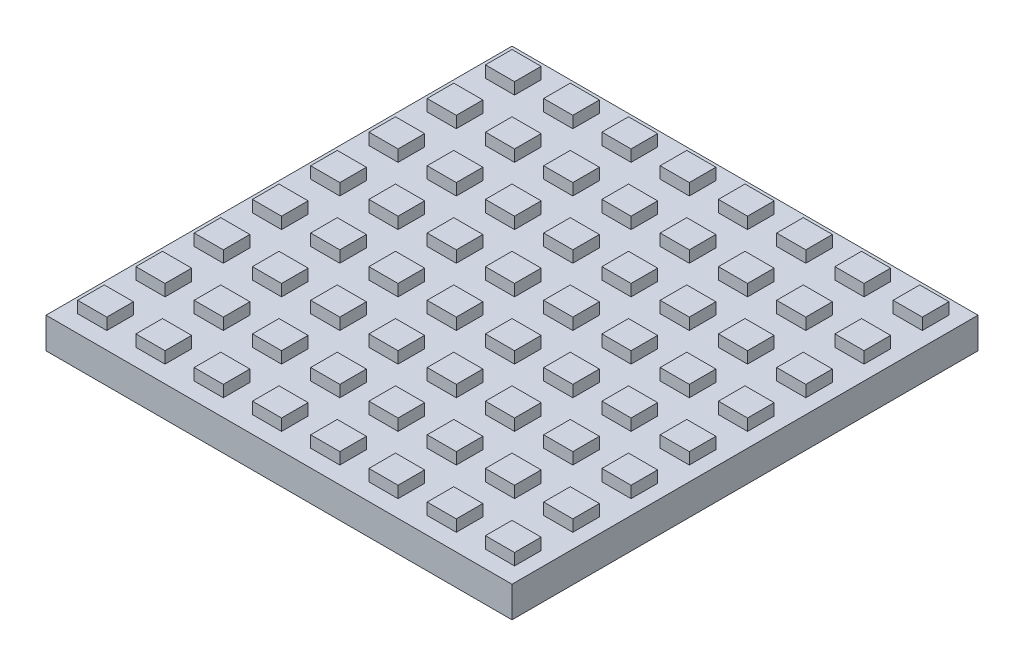
SolidWorks part; units mm, degrees
ref_plane "Front Plane" through (0, 0, 0) normal (0, 0, 1) x (1, 0, 0)
ref_plane "Top Plane" through (0, 0, 0) normal (0, 1, 0) x (1, 0, 0)
ref_plane "Right Plane" through (0, 0, 0) normal (1, 0, 0) x (0, 0, -1)
sketch "Sketch1" plane through (0, 0, 0) normal (0, 1, 0) x (1, 0, 0)
  line L1 (0, 0) -> (80, 0)
  line L2 (0, 0) -> (0, -80)
  line L3 (0, -80) -> (80, -80)
  line L4 (80, 0) -> (80, -80)
extrude "Boss-Extrude1" add sketch "Sketch1" along normal blind 5.3
sketch "Sketch2" plane through (0, 5.3, 0) normal (0, 1, 0) x (1, 0, 0)
  line L0 (0, 0) -> (5, 0) construction
  line L1 (80, 0) -> (0, 0) construction
  line L2 (5, 0) -> (5, -2.5) construction
  line L4 (2.5, -2.5) -> (7.5, -2.5)
  line L5 (2.5, -2.5) -> (2.5, -7.0645)
  line L6 (2.5, -7.0645) -> (7.5, -7.0645)
  line L7 (7.5, -2.5) -> (7.5, -7.0645)
extrude "Boss-Extrude2" add sketch "Sketch2" along normal blind 2
pattern_linear "LPattern1" count 8 spacing 10 along (1, 0, 0) count 8 spacing 10 along (0, 0, 1) of "Boss-Extrude2"
